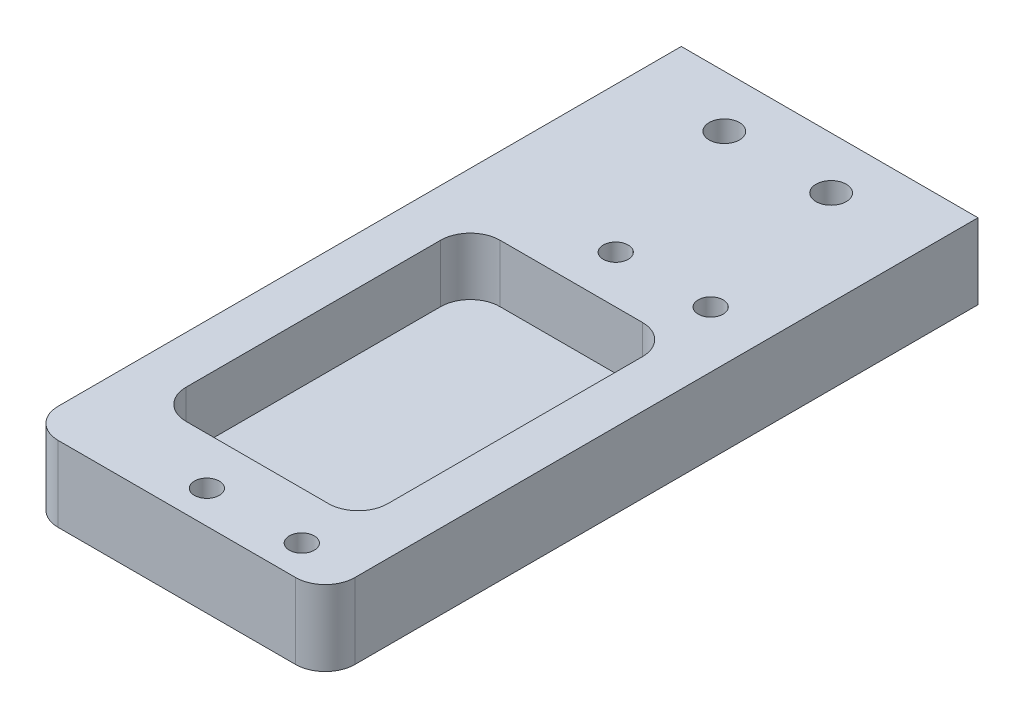
SolidWorks part; units mm, degrees
ref_plane "Front Plane" through (0, 0, 0) normal (0, 0, 1) x (1, 0, 0)
ref_plane "Top Plane" through (0, 0, 0) normal (0, 1, 0) x (1, 0, 0)
ref_plane "Right Plane" through (0, 0, 0) normal (1, 0, 0) x (0, 0, -1)
sketch "Sketch12" plane through (0, 0, 0) normal (0, 0, 1) x (1, 0, 0)
  line L1 (-25, -6.35) -> (25, -6.35)
  line L2 (-25, -6.35) -> (-25, 6.35)
  line L3 (-25, 6.35) -> (25, 6.35)
  line L4 (25, -6.35) -> (25, 6.35)
  line L5 (0, 6.35) -> (0, -6.35) construction
  line L6 (-25, 0) -> (25, 0) construction
  point P0 (0, 0)
  dimension "D1" = 12.7
  dimension "D2" = 50
extrude "Boss-Extrude1" add sketch "Sketch12" along normal blind 110
sketch "Sketch13" plane through (0, 0, 0) normal (0, 0, -1) x (-1, 0, 0)
  line L0 (-25, 0) -> (25, 0) construction
  line L1 (-25, -6.35) -> (-25, 6.35) construction
  line L2 (25, 6.35) -> (25, -6.35) construction
  point P6 (0, 0)
  point P7 (-17.5, 0)
  point P9 (17.5, 0)
  dimension "D1" = 7.5
  dimension "D2" = 7.5
  dimension "D3" = 35
hole_wizard "M5x0.8 Tapped Hole2" positions "Sketch14" profile "Sketch15" tap size "M5x0.8" standard "ANSI Metric"
sketch "Sketch14" plane through (0, 0, 0) normal (0, 0, -1) x (-1, 0, 0)
  point P0 (-17.5, 0)
  point P3 (0, 0)
  point P6 (17.5, 0)
sketch "Sketch15" plane through (17.5, 0, 0) normal (1, 0, 0) x (0, 1, 0)
  line L0 (0, 0) -> (0, 15.6618)
  line L1 (0, 15.6618) -> (2.1, 14.4)
  line L2 (2.1, 14.4) -> (2.1, 0)
  line L5 (2.1, 0) -> (0, 0)
  line L10 (0, 15.6618) -> (-2.1, 14.4) construction
  line L11 (0, -6.35) -> (0, 107.95) construction
  dimension "Tap Drill Dia." = 4.2
  dimension "Tap Drill Depth" = 14.4
  dimension "Drill Angle" = 118
cosmetic thread "Hole Thread1" parameters "D1"=12, "D2"=5
cosmetic thread "Hole Thread2" parameters "D1"=12, "D2"=5
cosmetic thread "Hole Thread3" parameters "D1"=12, "D2"=5
sketch "Sketch16" plane through (0, 6.35, 0) normal (0, 1, 0) x (1, 0, 0)
  line L0 (15.5, -35.55) -> (-0.5, -35.55) construction
  line L1 (-0.5, -35.55) -> (-0.5, -104.45) construction
  line L2 (-0.5, -104.45) -> (15.5, -104.45) construction
  line L3 (15.5, -104.45) -> (15.5, -35.55) construction
  line L4 (25, 0) -> (-25, 0) construction
  line L5 (25, -110) -> (25, 0) construction
  circle A0 centre (15.5, -35.55) radius 2.75 construction
  circle A1 centre (-0.5, -35.55) radius 2.75 construction
  circle A2 centre (15.5, -104.45) radius 2.75 construction
  circle A3 centre (-0.5, -104.45) radius 2.75 construction
  dimension "D1" = 35.55
  dimension "D4" = 5.5
  dimension "D2" = 68.9
  dimension "D3" = 16
  dimension "D5" = 9.5
hole_wizard "M5x0.8 Tapped Hole3" positions "Sketch17" profile "Sketch18" tap size "M5x0.8" standard "ANSI Metric" end condition through all
sketch "Sketch17" plane through (0, 6.35, 0) normal (0, 1, 0) x (1, 0, 0)
  point P0 (-0.5, -35.55)
  point P3 (15.5, -35.55)
  point P6 (15.5, -104.45)
  point P9 (-0.5, -104.45)
sketch "Sketch18" plane through (-0.5, 6.35, 35.55) normal (1, 0, 0) x (0, 0, 1)
  line L0 (0, 0) -> (0, 12.7)
  line L1 (0, 12.7) -> (2.1, 12.7)
  line L2 (2.1, 12.7) -> (2.1, 0)
  line L5 (2.1, 0) -> (0, 0)
  line L11 (0, -6.35) -> (0, 107.95) construction
  dimension "Thru Tap Drill Dia." = 4.2
  dimension "Thru Tap Drill Depth" = 12.7
cosmetic thread "Hole Thread4" parameters "D2"=5
cosmetic thread "Hole Thread5" parameters "D2"=5
cosmetic thread "Hole Thread6" parameters "D2"=5
cosmetic thread "Hole Thread7" parameters "D2"=5
sketch "Sketch19" [suppressed] plane through (0, 0, 0) normal (0, 0, -1) x (-1, 0, 0)
  line L4 (-25, 6.35) -> (-25, -6.35)
  line L5 (-25, -6.35) -> (25, -6.35)
  line L6 (25, -6.35) -> (25, 6.35)
  line L7 (25, 6.35) -> (-25, 6.35)
  line L8 (-25, 6.35) -> (-25, -6.35)
  line L9 (-25, -6.35) -> (25, -6.35)
  line L10 (25, -6.35) -> (25, 6.35)
  line L11 (25, 6.35) -> (-25, 6.35)
  dimension "D1" = 0
extrude "Boss-Extrude2" [suppressed] add sketch "Sketch19" along normal blind 60
sketch "Sketch20" [suppressed] plane through (-25, 0, 0) normal (-1, 0, 0) x (0, 0, 1)
  line L0 (-60, 0) -> (-10, 0) construction
  line L1 (-60, -6.35) -> (-60, 6.35) construction
  line L2 (-35, 0) -> (-35, 6.35) construction
  line L3 (112, 6.35) -> (-60, 6.35) construction
  circle A0 centre (-35, 0) radius 2.5
  circle A1 centre (-17, 0) radius 2.5
  circle A2 centre (-53, 0) radius 2.5
  dimension "D2" = 5
  dimension "D3" = 18
  dimension "D1" = 50
hole_wizard "M5x0.8 Tapped Hole4" [suppressed] positions "Sketch21" profile "Sketch22" tap size "M5x0.8" standard "ANSI Metric"
sketch "Sketch21" plane through (-25, 0, 0) normal (-1, 0, 0) x (0, 0, 1)
  point P0 (-53, 0)
  point P3 (-35, 0)
  point P6 (-17, 0)
sketch "Sketch22" plane through (-25, 0, -53) normal (0, 1, 0) x (0, 0, 1)
  line L0 (0, 0) -> (0, 25.2618)
  line L1 (0, 25.2618) -> (2.1, 24)
  line L2 (2.1, 24) -> (2.1, 0)
  line L5 (2.1, 0) -> (0, 0)
  line L10 (0, 25.2618) -> (-2.1, 24) construction
  line L11 (0, -6.35) -> (0, 107.95) construction
  dimension "Tap Drill Dia." = 4.2
  dimension "Tap Drill Depth" = 24
  dimension "Drill Angle" = 118
cosmetic thread "Hole Thread8" [suppressed] parameters "D1"=20, "D2"=5
cosmetic thread "Hole Thread9" [suppressed] parameters "D1"=20, "D2"=5
cosmetic thread "Hole Thread10" [suppressed] parameters "D1"=20, "D2"=5
sketch "Sketch23" plane through (0, -6.35, 0) normal (0, -1, 0) x (1, 0, 0)
  line L0 (-25, 8.75) -> (25, 8.75) construction
  line L1 (-25, 110) -> (-25, 0) construction
  line L2 (25, 110) -> (25, 0) construction
  line L3 (-25, 0) -> (25, 0) construction
  line L4 (0, 0) -> (0, 8.75) construction
  circle A0 centre (-9, 8.75) radius 2.55
  circle A1 centre (9, 8.75) radius 2.55
  dimension "D1" = 5.1
  dimension "D3" = 18
  dimension "D2" = 8.75
extrude "Cut-Extrude2" cut sketch "Sketch23" against normal through all contours A0 | A1
hole_wizard "M5x0.8 Tapped Hole5" [suppressed] positions "Sketch24" profile "Sketch25" tap size "M5x0.8" standard "ANSI Metric"
sketch "Sketch24" plane through (0, -6.35, 0) normal (0, -1, 0) x (-1, 0, 0)
  point P0 (9, -8.75)
  point P3 (-9, -8.75)
sketch "Sketch25" plane through (-9, -6.35, 8.75) normal (1, 0, 0) x (0, 0, -1)
  line L0 (0, 0) -> (0, 12.7)
  line L1 (0, 12.7) -> (2.1, 12.7)
  line L2 (2.1, 12.7) -> (2.1, 0)
  line L5 (2.1, 0) -> (0, 0)
  line L11 (0, -6.35) -> (0, 107.95) construction
  dimension "Thru Tap Drill Dia." = 4.2
  dimension "Thru Tap Drill Depth" = 12.7
sketch "Sketch26" plane through (0, 6.35, 0) normal (0, 1, 0) x (1, 0, 0)
  line L0 (25, -110) -> (25, 0) construction
  line L1 (-17, -43.55) -> (17, -43.55)
  line L2 (-17, -43.55) -> (-17, -96.45)
  line L3 (-17, -96.45) -> (17, -96.45)
  line L4 (17, -43.55) -> (17, -96.45)
  line L5 (0, -96.45) -> (0, -43.55) construction
  line L6 (-17, -70) -> (17, -70) construction
  line L7 (-25, -110) -> (-25, 0) construction
  circle A0 centre (-0.5, -35.55) radius 2.1 construction
  circle A1 centre (-0.5, -104.45) radius 2.1 construction
  point P132 (0, -70)
  dimension "D3" = 8
  dimension "D4" = 8
  dimension "D1" = 8
  dimension "D2" = 8
extrude "Cut-Extrude1" cut sketch "Sketch26" against normal blind 9.7
fillet "Fillet1" radius 5 6 edges at (-17, 1.5, 96.45) (17, 1.5, 96.45) (17, 1.5, 43.55) (-17, 1.5, 43.55) (25, 0, 110) (-25, 0, 110)
